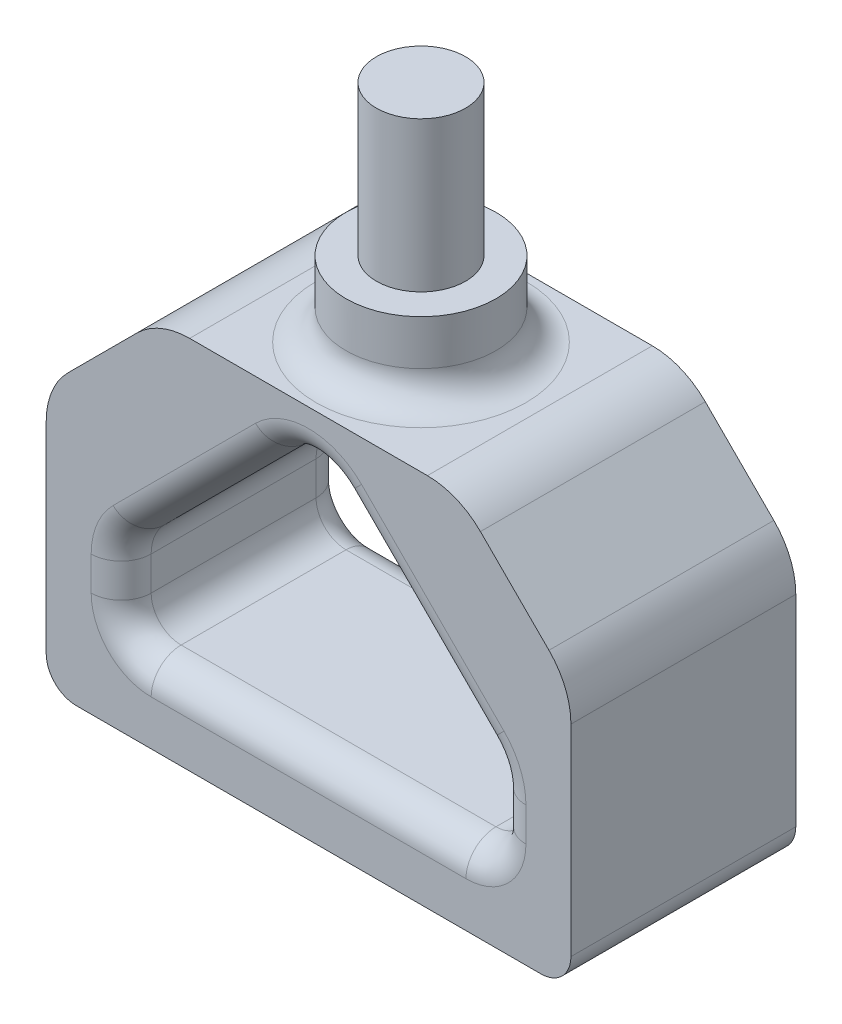
SolidWorks part; units mm, degrees
material "ABS"
ref_plane "Front Plane" through (0, 0, 0) normal (0, 0, 1) x (1, 0, 0)
ref_plane "Top Plane" through (0, 0, 0) normal (0, 1, 0) x (1, 0, 0)
ref_plane "Right Plane" through (0, 0, 0) normal (1, 0, 0) x (0, 0, -1)
sketch "Sketch3" plane through (0, 0, 0) normal (0, 1, 0) x (1, 0, 0)
  circle A0 centre (0, 0) radius 5
  dimension "D1" = 10
extrude "Boss-Extrude1" add sketch "Sketch3" along normal blind 5
sketch "Sketch4" plane through (0, 5, 0) normal (0, 1, 0) x (1, 0, 0)
  circle A0 centre (0, 0) radius 2.975
  dimension "D1" = 5.95
extrude "Boss-Extrude2" add sketch "Sketch4" along normal blind 10
sketch "Sketch8" plane through (0, 0, 0) normal (0, 0, 1) x (1, 0, 0)
  line L0 (5, 0) -> (5, 5) construction
  line L1 (-15.5, -25) -> (15.5, -25)
  line L2 (-17.5, -23) -> (-17.5, -9.5711)
  line L3 (-7.9289, 0) -> (7.9289, 0)
  line L4 (17.5, -23) -> (17.5, -9.5711)
  line L5 (-5, 5) -> (-5, 0) construction
  line L6 (5, 0) -> (5, 5) construction
  line L7 (-5, 5) -> (-5, 0) construction
  line L8 (0, 0) -> (0, -2) construction
  line L11 (-12.5, -15.7426) -> (-12.5, -18)
  line L12 (-10.5, -20) -> (10.5, -20)
  line L13 (12.5, -18) -> (12.5, -15.7426)
  line L14 (-2.1213, -4.1213) -> (-11.6213, -13.6213)
  line L15 (2.1213, -4.1213) -> (11.6213, -13.6213)
  line L18 (-11.4645, -1.4645) -> (-16.0355, -6.0355)
  line L19 (11.4645, -1.4645) -> (16.0355, -6.0355)
  arc A5 (-10.5, -20) -> (-12.5, -18) centre (-10.5, -18) cw
  arc A6 (10.5, -20) -> (12.5, -18) centre (10.5, -18) ccw
  arc A7 (15.5, -25) -> (17.5, -23) centre (15.5, -23) ccw
  arc A8 (-15.5, -25) -> (-17.5, -23) centre (-15.5, -23) cw
  arc A9 (2.1213, -4.1213) -> (-2.1213, -4.1213) centre (0, -6.2426) ccw
  arc A10 (12.5, -15.7426) -> (11.6213, -13.6213) centre (9.5, -15.7426) ccw
  arc A11 (-12.5, -15.7426) -> (-11.6213, -13.6213) centre (-9.5, -15.7426) cw
  arc A16 (-17.5, -9.5711) -> (-16.0355, -6.0355) centre (-12.5, -9.5711) cw
  arc A17 (17.5, -9.5711) -> (16.0355, -6.0355) centre (12.5, -9.5711) ccw
  arc A18 (7.9289, 0) -> (11.4645, -1.4645) centre (7.9289, -5) cw
  arc A19 (-7.9289, 0) -> (-11.4645, -1.4645) centre (-7.9289, -5) ccw
  point P17 (17.5, 0)
  point P35 (17.5, -25)
  point P38 (-17.5, -25)
  point P43 (-10, 0)
  dimension "D9" = 3
  dimension "D10" = 45
  dimension "D13" = 5
  dimension "D1" = 25
  dimension "D2" = 35
  dimension "D3" = 2
  dimension "D4" = 5
  dimension "D5" = 5
  dimension "D6" = 45
  dimension "D7" = 45
  dimension "D8" = 5
  dimension "D11" = 45
  dimension "D12" = 5
extrude "Boss-Extrude5" add sketch "Sketch8" along normal mid plane 15
fillet "Fillet5" radius 2 1 edges at (0, 0, -5)
fillet "Fillet6" radius 2 20 edges at (-11.9142, -19.4142, -7.5) (-12.5, -16.8713, -7.5) (12.5, -16.8713, -7.5) (11.9142, -19.4142, -7.5) (-11.9142, -19.4142, 7.5) (-12.5, -16.8713, 7.5) (12.5, -16.8713, 7.5) (11.9142, -19.4142, 7.5) (0, -20, -7.5) (0, -20, 7.5) (-12.2716, -14.5946, -7.5) (-6.8713, -8.8713, -7.5) (0, -3.2426, -7.5) (6.8713, -8.8713, -7.5) (12.2716, -14.5946, -7.5) (-12.2716, -14.5946, 7.5) (-6.8713, -8.8713, 7.5) (0, -3.2426, 7.5) (6.8713, -8.8713, 7.5) (12.2716, -14.5946, 7.5)
